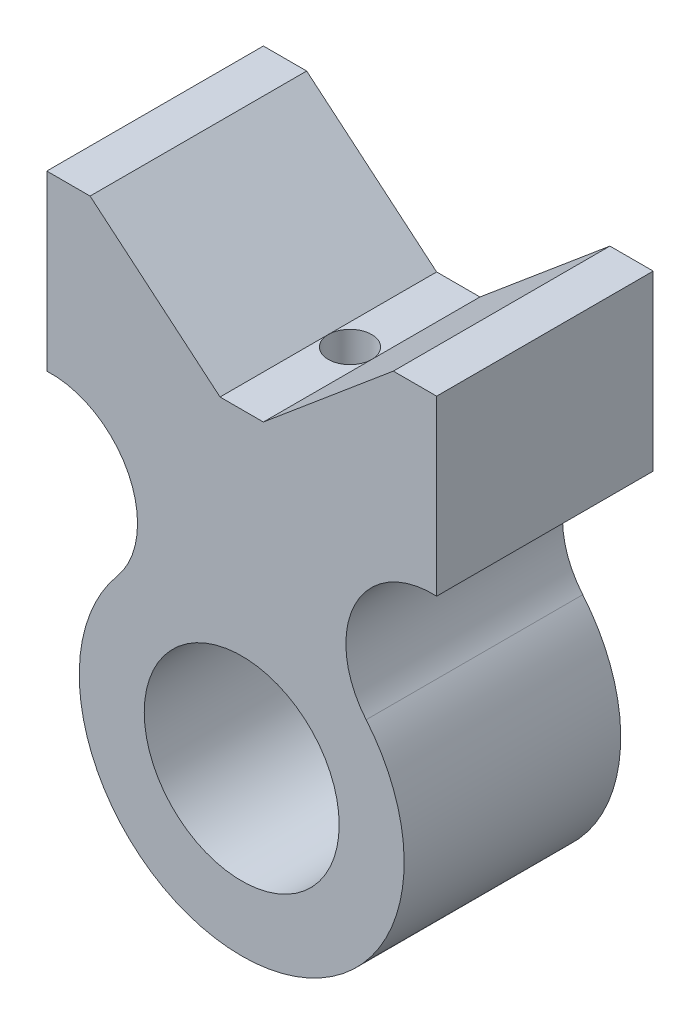
SolidWorks part; units mm, degrees
material "Nylon 101"
ref_plane "Front Plane" through (0, 0, 0) normal (0, 0, 1) x (1, 0, 0)
ref_plane "Top Plane" through (0, 0, 0) normal (0, 1, 0) x (1, 0, 0)
ref_plane "Right Plane" through (0, 0, 0) normal (1, 0, 0) x (0, 0, -1)
sketch "Sketch1" plane through (0, 0, 0) normal (0, 0, 1) x (1, 0, 0)
  line L0 (0, 0) -> (57.4533, 48.2091) construction
  line L1 (0, 0) -> (-58.9769, 49.4875) construction
  line L2 (0, 0) -> (0, 77.5) construction
  line L3 (45, 56.9376) -> (45, 96.9376)
  line L4 (35, 96.9376) -> (5, 71.7646)
  line L5 (5, 71.7646) -> (-5, 71.7646)
  line L6 (35, 96.9376) -> (45, 96.9376)
  line L7 (-35, 96.9376) -> (-5, 71.7646)
  line L8 (-35, 96.9376) -> (-45, 96.9376)
  line L9 (-45, 56.9376) -> (-45, 96.9376)
  arc A0 (-28.7267, 24.1045) -> (28.7267, 24.1045) centre (0, 0) ccw
  circle A1 centre (0, 0) radius 22.5
  arc A2 (28.7267, 24.1045) -> (45, 56.9376) centre (44.0476, 36.9603) cw
  arc A3 (-28.7267, 24.1045) -> (-45, 56.9376) centre (-44.0476, 36.9603) ccw
  point P4 (26.1279, 45.842)
  point P8 (28.7267, 62.9982)
  point P16 (28.7267, 71.8383)
  point P17 (0, 0)
  point P18 (12.4392, 55.5137)
  point P19 (0, 0)
  point P20 (0, 0)
  point P21 (28.7267, 69.1776)
  point P23 (0, 71.7646)
  dimension "D1" = 75
  dimension "D2" = 45
  dimension "D3" = 100
  dimension "D4" = 77.5
  dimension "D6" = 20
  dimension "D7" = 40
  dimension "D8" = 10
  dimension "D9" = 35
  dimension "D10" = 5
  dimension "D11" = 100
extrude "Boss-Extrude1" add sketch "Sketch1" along normal blind 50
sketch "Sketch2" plane through (0, 71.7646, 0) normal (0, 1, 0) x (1, 0, 0)
  line L0 (5, -50) -> (-5, -50) construction
  circle A0 centre (0, -25) radius 5
  dimension "D1" = 25
extrude "Cut-Extrude1" cut sketch "Sketch2" against normal up to next
